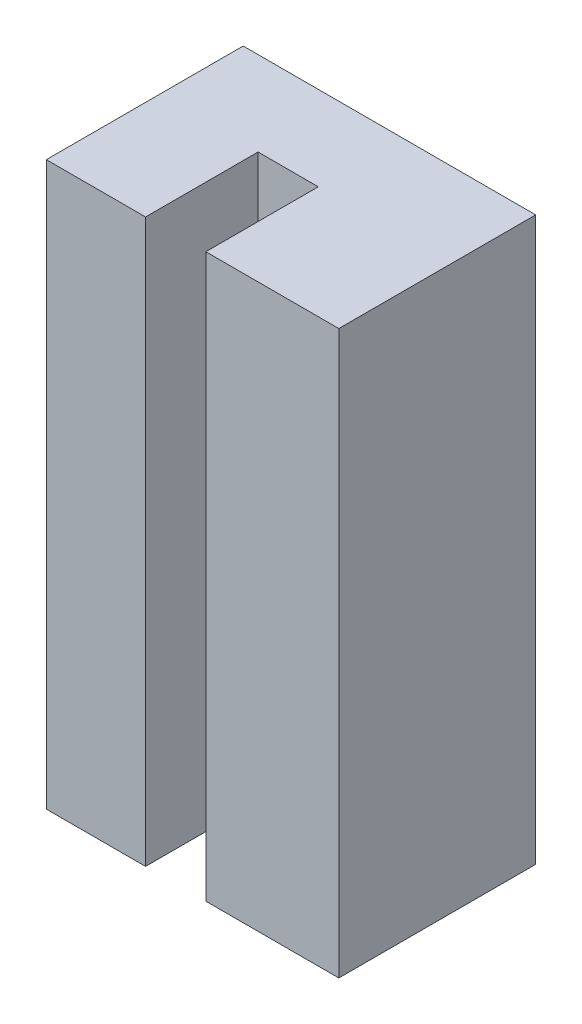
SolidWorks part; units mm, degrees
ref_plane "Front Plane" through (0, 0, 0) normal (0, 0, 1) x (1, 0, 0)
ref_plane "Top Plane" through (0, 0, 0) normal (0, 1, 0) x (1, 0, 0)
ref_plane "Right Plane" through (0, 0, 0) normal (1, 0, 0) x (0, 0, -1)
sketch "Эскиз1" plane through (0, 0, 0) normal (0, 1, 0) x (1, 0, 0)
  line L1 (0, 0) -> (5.2, 0)
  line L2 (0, 0) -> (0, 3.5)
  line L3 (0, 3.5) -> (5.2, 3.5)
  line L4 (5.2, 0) -> (5.2, 3.5)
  dimension "D1" = 5.2
  dimension "D2" = 3.5
extrude "Бобышка-Вытянуть1" add sketch "Эскиз1" along normal blind 10
sketch "Эскиз2" plane through (0, 10, 0) normal (0, 1, 0) x (1, 0, 0)
  line L4 (0, 3.5) -> (0, 0)
  line L5 (0, 0) -> (5.2, 0)
  line L6 (5.2, 0) -> (5.2, 3.5)
  line L7 (5.2, 3.5) -> (0, 3.5)
  line L8 (0, 3.5) -> (0, 0)
  line L9 (0, 0) -> (5.2, 0)
  line L10 (5.2, 0) -> (5.2, 3.5)
  line L11 (5.2, 3.5) -> (0, 3.5)
  line L12 (1.7641, 2) -> (1.7641, -27.6)
  line L13 (2.8352, 2) -> (1.7641, 2)
  line L14 (2.8352, -27.6) -> (2.8352, 2)
  line L15 (1.7641, -27.6) -> (2.8352, -27.6)
  line L16 (1.7641, 2) -> (1.7641, -27.6)
  line L17 (2.8352, 2) -> (1.7641, 2)
  line L18 (2.8352, -27.6) -> (2.8352, 2)
  line L19 (1.7641, -27.6) -> (2.8352, -27.6)
  dimension "D1" = 0
  dimension "D2" = 0
extrude "Вырез-Вытянуть1" cut sketch "Эскиз2" against normal blind 10 contours L9 L18 L17 L16
